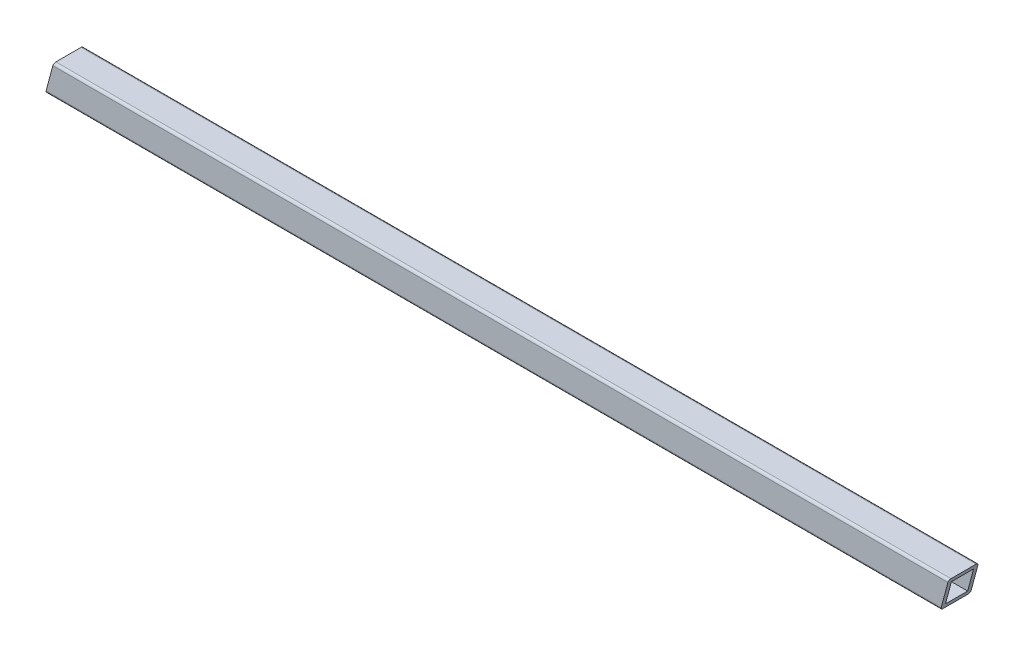
SolidWorks part; units mm, degrees
material "Plain Carbon Steel"
ref_plane "Front Plane" through (0, 0, 0) normal (0, 0, 1) x (1, 0, 0)
ref_plane "Top Plane" through (0, 0, 0) normal (0, 1, 0) x (1, 0, 0)
ref_plane "Right Plane" through (0, 0, 0) normal (1, 0, 0) x (0, 0, -1)
sketch "Sketch1" plane through (0, 0, 0) normal (1, 0, 0) x (0, 0, -1)
  line L0 (0, 2.54) -> (0, 29.21)
  line L1 (-2.54, 31.75) -> (-29.21, 31.75)
  line L2 (-31.75, 29.21) -> (-31.75, 2.54)
  line L3 (-29.21, 0) -> (-2.54, 0)
  line L4 (-4.1275, 4.1275) -> (-4.1275, 27.6225)
  line L5 (-4.1275, 27.6225) -> (-27.6225, 27.6225)
  line L6 (-27.6225, 27.6225) -> (-27.6225, 4.1275)
  line L7 (-27.6225, 4.1275) -> (-4.1275, 4.1275)
  arc A0 (-31.75, 2.54) -> (-29.21, 0) centre (-29.21, 2.54) ccw
  arc A1 (0, 2.54) -> (-2.54, 0) centre (-2.54, 2.54) cw
  arc A2 (0, 29.21) -> (-2.54, 31.75) centre (-2.54, 29.21) ccw
  arc A3 (-31.75, 29.21) -> (-29.21, 31.75) centre (-29.21, 29.21) cw
  arc A4 (-4.1275, 27.6225) -> (-4.1275, 27.6225) centre (-4.1275, 27.6225) ccw
  arc A5 (-27.6225, 27.6225) -> (-27.6225, 27.6225) centre (-27.6225, 27.6225) cw
  arc A6 (-27.6225, 4.1275) -> (-27.6225, 4.1275) centre (-27.6225, 4.1275) ccw
  arc A7 (-4.1275, 4.1275) -> (-4.1275, 4.1275) centre (-4.1275, 4.1275) cw
  point P12 (0, 0)
  point P15 (0, 31.75)
  point P18 (-31.75, 31.75)
  dimension "D3" = 2.54
  dimension "D1" = 31.75
  dimension "D2" = 31.75
  dimension "D4" = 4.1275
extrude "Boss-Extrude1" add sketch "Sketch1" along normal blind 1320.8
sketch "Sketch2" plane through (1320.8, 0, 0) normal (1, 0, 0) x (0, 0, -1)
  line L0 (-31.75, 15.875) -> (0, 15.875)
  line L1 (-31.75, 29.21) -> (-31.75, 2.54) construction
  line L2 (0, 2.54) -> (0, 29.21) construction
scale "Scale2" scale about centroid uniform scaling no x scale factor 1 y scale factor 0.4 z scale factor 0.4
sketch "Sketch3" plane through (0, 0, 22.225) normal (0, 0, 1) x (1, 0, 0)
  line L6 (861.3548, 22.225) -> (857.9518, 9.525)
  line L7 (1320.8, 22.225) -> (0, 22.225) construction
  line L9 (1320.8, 9.525) -> (0, 9.525) construction
  line L10 (861.3548, 22.225) -> (846.9636, 22.225)
  line L11 (846.9636, 22.225) -> (846.9636, 9.525)
  line L12 (846.9636, 9.525) -> (857.9518, 9.525)
  point P4 (861.3548, 22.225)
  dimension "D1" = 105
extrude "Cut-Extrude1" cut sketch "Sketch3" against normal through all
sketch "Sketch4" plane through (0, 0, 22.225) normal (0, 0, 1) x (1, 0, 0)
  line L0 (1236.8399, 9.525) -> (1320.8, 9.525)
  line L1 (1320.8, 9.525) -> (1320.8, 22.225)
  line L2 (1320.8, 22.225) -> (1240.2429, 22.225)
  line L4 (1320.8, 22.225) -> (861.3548, 22.225) construction
  line L5 (1240.2429, 22.225) -> (1236.8399, 9.525)
  line L7 (1320.8, 9.525) -> (857.9518, 9.525) construction
  dimension "D1" = 80.5571
  dimension "D2" = 105
extrude "Cut-Extrude2" cut sketch "Sketch4" against normal through all
sketch "Sketch5" plane through (0, 0, 22.225) normal (0, 0, 1) x (1, 0, 0)
  line L0 (859.6533, 15.875) -> (1238.5414, 15.875) construction
  line L1 (858.2241, 10.541) -> (861.0825, 21.209) construction
  line L2 (1239.9706, 21.209) -> (1237.1122, 10.541) construction
